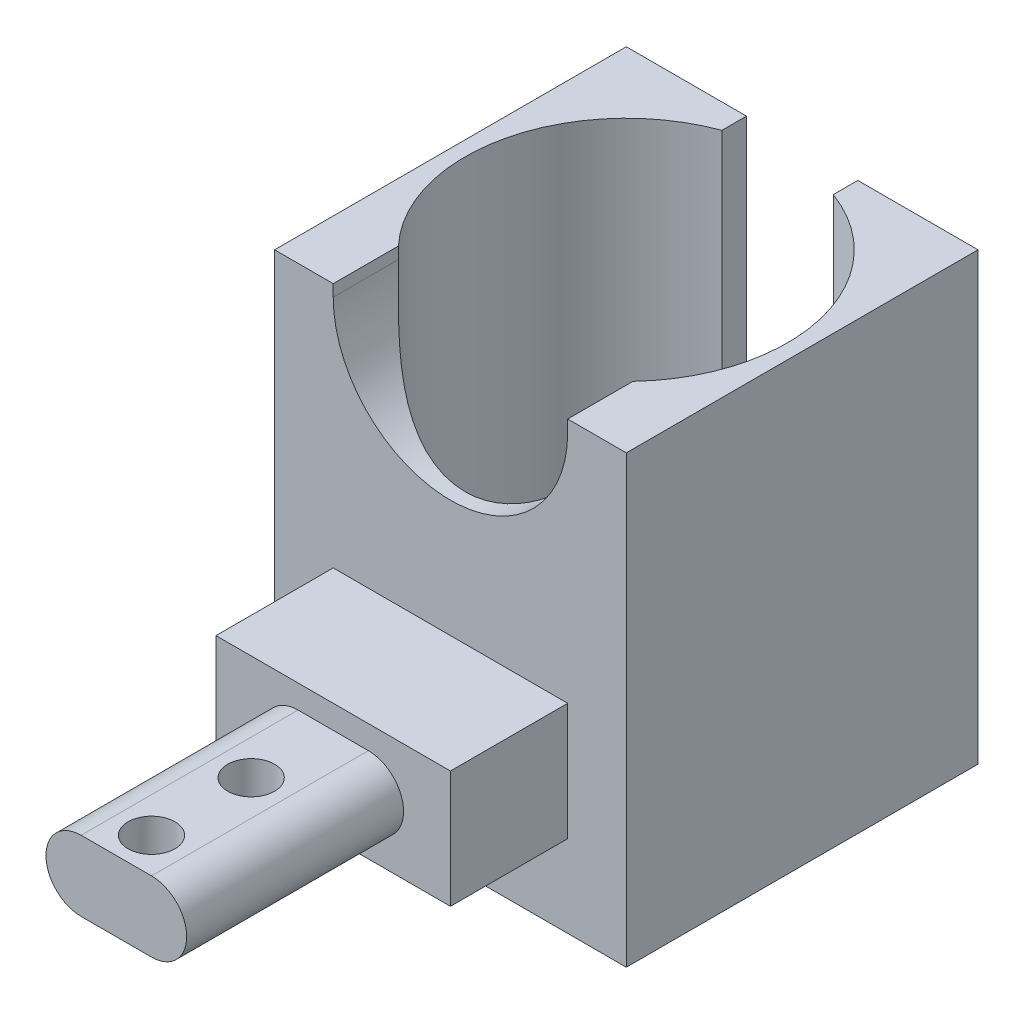
SolidWorks part; units mm, degrees
ref_plane "Ebene vorne" through (0, 0, 0) normal (0, 0, 1) x (1, 0, 0)
ref_plane "Ebene oben" through (0, 0, 0) normal (0, 1, 0) x (1, 0, 0)
ref_plane "Ebene rechts" through (0, 0, 0) normal (1, 0, 0) x (0, 0, -1)
sketch "Sketch1" plane through (0, 0, 0) normal (0, 0, 1) x (1, 0, 0)
  line L1 (-15, 18) -> (15, 18)
  line L2 (-15, 18) -> (-15, -18)
  line L3 (-15, -18) -> (15, -18)
  line L4 (15, 18) -> (15, -18)
  line L5 (0, -18) -> (0, 18) construction
  line L6 (-15, 0) -> (15, 0) construction
  point P0 (0, 0)
  dimension "D1" = 30
  dimension "D2" = 36
extrude "Boss-Extrude1" add sketch "Sketch1" along normal blind 30
sketch "Sketch2" plane through (0, 0, 30) normal (0, 0, 1) x (1, 0, 0)
  line L0 (-15, -18) -> (15, -18) construction
  line L1 (-10, -3) -> (10, -3)
  line L2 (-10, -3) -> (-10, -13)
  line L3 (-10, -13) -> (10, -13)
  line L4 (10, -3) -> (10, -13)
  line L5 (0, -13) -> (0, -3) construction
  line L6 (-10, -8) -> (10, -8) construction
  line L7 (-15, 18) -> (-15, -18) construction
  point P0 (0, -8)
  dimension "D1" = 20
  dimension "D2" = 10
  dimension "D3" = 5
  dimension "D4" = 5
extrude "Boss-Extrude2" add sketch "Sketch2" along normal blind 10
sketch "Sketch3" plane through (0, 0, 40) normal (0, 0, 1) x (1, 0, 0)
  line L0 (-3, -8) -> (3, -8) construction
  line L1 (-3, -5) -> (3, -5)
  line L2 (-3, -11) -> (3, -11)
  line L4 (10, -3) -> (-10, -3) construction
  line L5 (10, -13) -> (10, -3) construction
  arc A0 (-3, -5) -> (-3, -11) centre (-3, -8) ccw
  arc A1 (3, -11) -> (3, -5) centre (3, -8) ccw
  point P2 (0, -8)
  dimension "D2" = 6
  dimension "D4" = 7
  dimension "D1" = 6
  dimension "D3" = 2
extrude "Boss-Extrude3" add sketch "Sketch3" along normal blind 18.5
sketch "Sketch4" plane through (0, 18, 0) normal (0, 1, 0) x (1, 0, 0)
  line L0 (15, -30) -> (-15, -30) construction
  line L1 (15, -30) -> (15, 0) construction
  circle A0 centre (0, -15) radius 13.75
  dimension "D2" = 15
  dimension "D3" = 27.5
  dimension "D1" = 15
extrude "Cut-Extrude2" cut sketch "Sketch4" against normal up to next
sketch "Sketch6" plane through (0, 0, 0) normal (0, 0, -1) x (-1, 0, 0)
  line L5 (0, -2.25) -> (0, 18) construction
  line L6 (-4.75, -2.25) -> (-4.75, 18)
  line L8 (4.75, -2.25) -> (4.75, 18)
  line L10 (15, -18) -> (-15, -18) construction
  line L11 (-15, 18) -> (15, 18) construction
  arc A0 (-4.75, -2.25) -> (4.75, -2.25) centre (0, -2.25) ccw
  arc A1 (4.75, 18) -> (-4.75, 18) centre (0, 18) ccw
  point P1 (0, 7.875)
  dimension "D2" = 15.75
  dimension "D1" = 9.5
  dimension "D3" = 0
extrude "Cut-Extrude5" cut sketch "Sketch6" against normal up to next
sketch "Sketch8" plane through (0, 0, 30) normal (0, 0, 1) x (1, 0, 0)
  line L0 (0, 17) -> (0, 18) construction
  line L1 (-10, 17) -> (-10, 18)
  line L2 (10, 17) -> (10, 18)
  line L3 (-15, -18) -> (15, -18) construction
  line L4 (15, -18) -> (15, 18) construction
  line L6 (15, 18) -> (-15, 18) construction
  arc A0 (-10, 17) -> (10, 17) centre (0, 17) ccw
  arc A1 (10, 18) -> (-10, 18) centre (0, 18) ccw
  point P2 (0, 17.5)
  dimension "D1" = 20
  dimension "D2" = 35
  dimension "D3" = 15
  dimension "D4" = 0
extrude "Cut-Extrude6" cut sketch "Sketch8" against normal up to next
sketch "Sketch9" plane through (0, -18, 0) normal (0, -1, 0) x (1, 0, 0)
  line L0 (3, 58.5) -> (-3, 58.5) construction
  line L1 (-3, 58.5) -> (-3, 40) construction
  circle A0 centre (0, 55.5) radius 2
  circle A1 centre (0, 47) radius 2
  dimension "D2" = 4
  dimension "D5" = 4
  dimension "D1" = 3
  dimension "D3" = 3
  dimension "D4" = 3
  dimension "D6" = 8.5
extrude "Cut-Extrude7" cut sketch "Sketch9" against normal up to next
sketch "Sketch10" plane through (0, -18, 0) normal (0, -1, 0) x (-1, 0, 0)
  line L0 (-15, -30) -> (-15, 0) construction
  line L1 (-15, -30) -> (15, -30)
  line L2 (-15, -30) -> (-15, 0)
  line L3 (-15, 0) -> (15, 0)
  line L4 (15, -30) -> (15, 0)
  line L5 (0, 0) -> (0, -30) construction
  line L6 (-15, -15) -> (15, -15) construction
  line L7 (15, -30) -> (15, 0) construction
  line L8 (15, -30) -> (-15, -30) construction
  line L9 (15, 0) -> (-15, 0) construction
  point P0 (0, -15)
  dimension "D1" = 0
  dimension "D2" = 0
  dimension "D3" = 0
  dimension "D4" = 0
extrude "Boss-Extrude4" add sketch "Sketch10" along normal blind 2
sketch "Sketch11" plane through (0, -18, 0) normal (0, 1, 0) x (1, 0, 0)
  line L0 (15, -30) -> (-15, -30) construction
  circle A0 centre (0, -15) radius 13.25
  dimension "D2" = 26.5
  dimension "D1" = 0
  dimension "D3" = 15
extrude "Cut-Extrude8" cut sketch "Sketch11" against normal up to next
